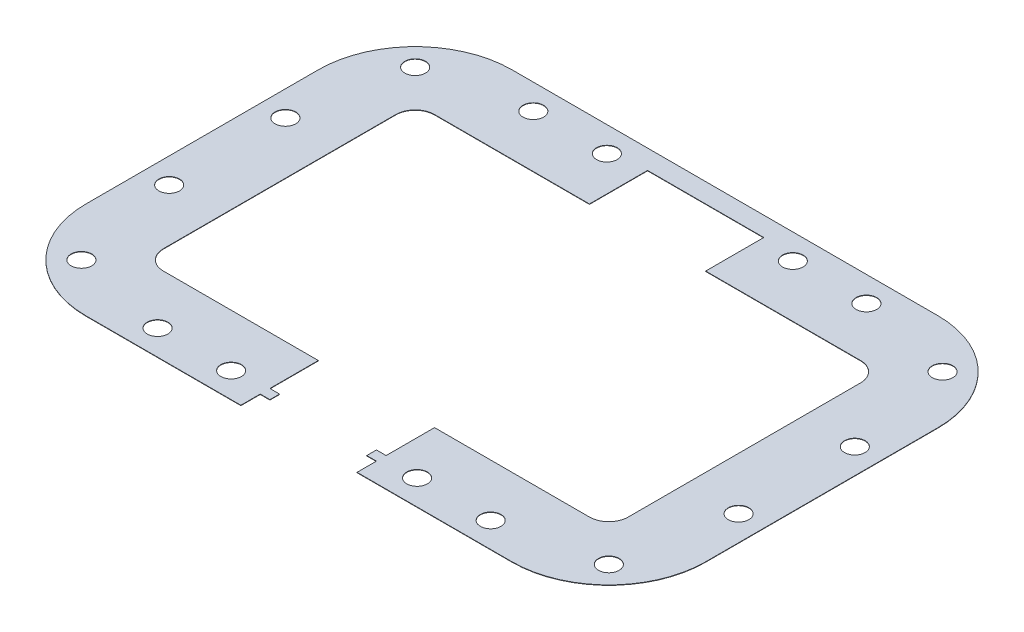
SolidWorks part; units mm, degrees
ref_plane "Front" through (0, 0, 0) normal (0, 0, 1) x (1, 0, 0)
ref_plane "Top" through (0, 0, 0) normal (0, 1, 0) x (1, 0, 0)
ref_plane "Right" through (0, 0, 0) normal (1, 0, 0) x (0, 0, -1)
sketch "Sketch1" plane through (0, 0, 0) normal (0, 1, 0) x (1, 0, 0)
  line L0 (19.05, 44.45) -> (69.85, 44.45)
  line L1 (-69.85, -69.85) -> (-19.05, -69.85)
  line L2 (-101.6, -38.1) -> (-101.6, 38.1)
  line L3 (-69.85, 69.85) -> (69.85, 69.85)
  line L4 (101.6, -38.1) -> (101.6, 38.1)
  line L5 (-101.6, -69.85) -> (101.6, 69.85) construction
  line L6 (-101.6, 69.85) -> (101.6, -69.85) construction
  line L7 (-69.85, -44.45) -> (-19.05, -44.45)
  line L8 (-76.2, -38.1) -> (-76.2, 38.1)
  line L9 (-69.85, 44.45) -> (-19.05, 44.45)
  line L10 (76.2, -38.1) -> (76.2, 38.1)
  line L11 (-76.2, -44.45) -> (76.2, 44.45) construction
  line L12 (-76.2, 44.45) -> (76.2, -44.45) construction
  line L13 (0, 63.5) -> (0, 0) construction
  line L14 (-19.05, 44.45) -> (-19.05, 63.5)
  line L15 (-19.05, 63.5) -> (19.05, 63.5)
  line L16 (19.05, 44.45) -> (19.05, 63.5)
  line L17 (-19.05, -69.85) -> (-19.05, -63.5)
  line L18 (19.05, -69.85) -> (19.05, -63.5)
  line L19 (-19.05, -63.5) -> (-15.875, -63.5)
  line L20 (19.05, -63.5) -> (15.875, -63.5)
  line L21 (-15.875, -63.5) -> (-15.875, -60.325)
  line L22 (15.875, -63.5) -> (15.875, -60.325)
  line L23 (-15.875, -60.325) -> (-19.05, -60.325)
  line L24 (15.875, -60.325) -> (19.05, -60.325)
  line L25 (-19.05, -60.325) -> (-19.05, -44.45)
  line L26 (19.05, -60.325) -> (19.05, -44.45)
  line L27 (19.05, -44.45) -> (69.85, -44.45)
  line L28 (19.05, -69.85) -> (69.85, -69.85)
  arc A0 (-69.85, -69.85) -> (-101.6, -38.1) centre (-69.85, -38.1) cw
  arc A1 (-101.6, 38.1) -> (-69.85, 69.85) centre (-69.85, 38.1) cw
  arc A2 (69.85, -69.85) -> (101.6, -38.1) centre (69.85, -38.1) ccw
  arc A3 (69.85, 69.85) -> (101.6, 38.1) centre (69.85, 38.1) cw
  arc A4 (69.85, -44.45) -> (76.2, -38.1) centre (69.85, -38.1) ccw
  arc A5 (69.85, 44.45) -> (76.2, 38.1) centre (69.85, 38.1) cw
  arc A6 (-69.85, -44.45) -> (-76.2, -38.1) centre (-69.85, -38.1) cw
  arc A7 (-76.2, 38.1) -> (-69.85, 44.45) centre (-69.85, 38.1) cw
  point P0 (0, 0)
  point P18 (0, 0)
  dimension "D3" = 31.75
  dimension "D6" = 6.35
  dimension "D1" = 203.2
  dimension "D2" = 139.7
  dimension "D4" = 88.9
  dimension "D5" = 152.4
  dimension "D7" = 6.35
  dimension "D8" = 38.1
  dimension "D9" = 31.75
  dimension "D10" = 38.1
  dimension "D11" = 6.35
  dimension "D12" = 3.175
extrude "Boss-Extrude1" add sketch "Sketch1" along normal blind 0.127
sketch "Sketch2" plane through (0, 0.127, 0) normal (0, 1, 0) x (1, 0, 0)
  line L6 (0, 0) -> (0, 49.3938) construction
  line L10 (-69.85, -61.595) -> (-19.05, -61.595)
  line L11 (-93.345, 38.1) -> (-93.345, -38.1)
  line L12 (19.05, -61.595) -> (69.85, -61.595)
  line L13 (93.345, -38.1) -> (93.345, 38.1)
  line L14 (69.85, 61.595) -> (-69.85, 61.595)
  line L15 (-69.85, -61.595) -> (-19.05, -61.595) construction
  line L16 (-93.345, 38.1) -> (-93.345, -38.1) construction
  line L17 (19.05, -61.595) -> (69.85, -61.595) construction
  line L18 (93.345, -38.1) -> (93.345, 38.1) construction
  line L19 (69.85, 61.595) -> (-69.85, 61.595) construction
  circle A4 centre (-30.48, 61.595) radius 3.3782
  circle A5 centre (-54.61, 61.595) radius 3.3782
  circle A6 centre (30.48, -61.595) radius 3.3782
  circle A7 centre (54.61, -61.595) radius 3.3782
  arc A8 (-93.345, -38.1) -> (-69.85, -61.595) centre (-69.85, -38.1) ccw
  arc A9 (-69.85, 61.595) -> (-93.345, 38.1) centre (-69.85, 38.1) ccw
  arc A10 (69.85, -61.595) -> (93.345, -38.1) centre (69.85, -38.1) ccw
  arc A11 (93.345, 38.1) -> (69.85, 61.595) centre (69.85, 38.1) ccw
  arc A12 (-93.345, -38.1) -> (-69.85, -61.595) centre (-69.85, -38.1) ccw construction
  arc A13 (-69.85, 61.595) -> (-93.345, 38.1) centre (-69.85, 38.1) ccw construction
  arc A14 (69.85, -61.595) -> (93.345, -38.1) centre (69.85, -38.1) ccw construction
  arc A15 (93.345, 38.1) -> (69.85, 61.595) centre (69.85, 38.1) ccw construction
  circle A16 centre (86.4635, -54.7135) radius 3.3782
  circle A17 centre (-86.4635, 54.7135) radius 3.3782
  circle A18 centre (-93.345, 19.05) radius 3.3782
  circle A19 centre (-93.345, -19.05) radius 3.3782
  circle A20 centre (93.345, -19.05) radius 3.3782
  circle A21 centre (93.345, 19.05) radius 3.3782
  circle A22 centre (86.4635, 54.7135) radius 3.3782
  circle A23 centre (-86.4635, -54.7135) radius 3.3782
  circle A24 centre (-54.61, -61.595) radius 3.3782
  circle A25 centre (-30.48, -61.595) radius 3.3782
  circle A26 centre (54.61, 61.595) radius 3.3782
  circle A27 centre (30.48, 61.595) radius 3.3782
  dimension "D2" = 6.7564
  dimension "D3" = 38.1
  dimension "D4" = 19.05
  dimension "D6" = 54.61
  dimension "D5" = 30.48
  dimension "D1" = 8.255
extrude "Cut-Extrude1" cut sketch "Sketch2" against normal through all
